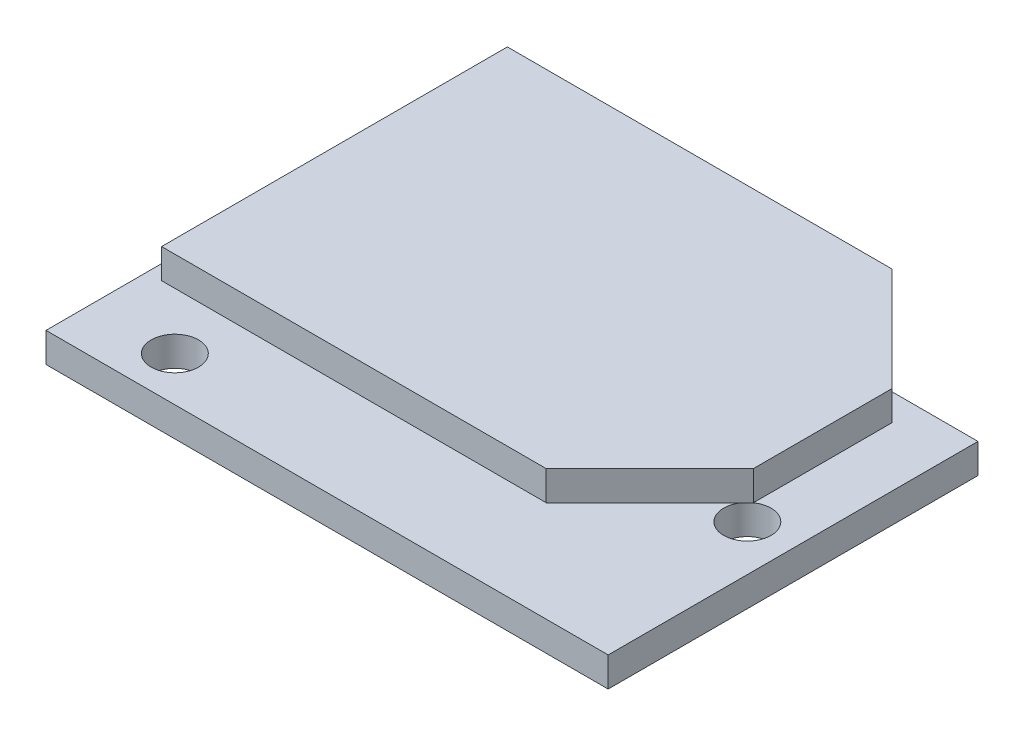
SolidWorks part; units mm, degrees
ref_plane "Ebene vorne" through (0, 0, 0) normal (0, 0, 1) x (1, 0, 0)
ref_plane "Ebene oben" through (0, 0, 0) normal (0, 1, 0) x (1, 0, 0)
ref_plane "Ebene rechts" through (0, 0, 0) normal (1, 0, 0) x (0, 0, -1)
sketch "Sketch1" plane through (0, 0, 0) normal (0, 1, 0) x (1, 0, 0)
  line L0 (-10.3687, 0) -> (25.2304, 0) construction
  line L2 (0, 12.5) -> (38, 12.5)
  line L3 (0, 12.5) -> (0, -12.5)
  line L4 (0, -12.5) -> (38, -12.5)
  line L5 (38, 12.5) -> (38, -12.5)
  circle A0 centre (5.71, 9.5) radius 1.6
  circle A1 centre (5.71, -9.5) radius 1.6
  circle A2 centre (34.91, 0) radius 1.6
  dimension "D4" = 3.2
  dimension "D5" = 3.2
  dimension "D1" = 25
  dimension "D2" = 38
  dimension "D3" = 19
  dimension "D6" = 5.71
  dimension "D7" = 29.2
extrude "Boss-Extrude1" add sketch "Sketch1" along normal blind 2
sketch "Sketch2" plane through (0, 2, 0) normal (0, 1, 0) x (1, 0, 0)
  line L0 (33, -11.6864) -> (40, -4.6864)
  line L1 (7, 11.6864) -> (33, 11.6864)
  line L2 (7, 11.6864) -> (7, -11.6864)
  line L3 (7, -11.6864) -> (33, -11.6864)
  line L4 (3.4909, 0) -> (48.4454, 0) construction
  line L5 (40, -4.6864) -> (40, 4.6864)
  line L6 (40, 4.6864) -> (33, 11.6864)
  line L7 (0, 12.5) -> (0, -12.5) construction
  line L8 (38, -12.5) -> (38, 12.5) construction
  dimension "D1" = 45
  dimension "D2" = 26
  dimension "D3" = 7
  dimension "D4" = 2
  dimension "D5" = 45
extrude "Boss-Extrude2" add sketch "Sketch2" along normal blind 2 from offset 6 separate body
